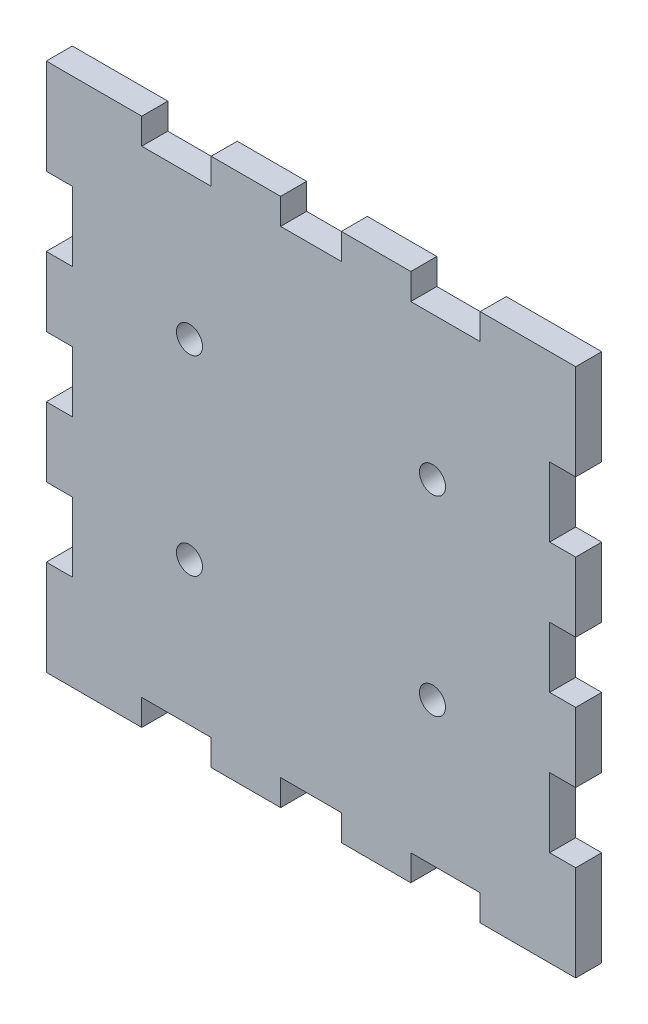
SolidWorks part; units mm, degrees
material "Beech"
ref_plane "Front Plane" through (0, 0, 0) normal (0, 0, 1) x (1, 0, 0)
ref_plane "Top Plane" through (0, 0, 0) normal (0, 1, 0) x (1, 0, 0)
ref_plane "Right Plane" through (0, 0, 0) normal (1, 0, 0) x (0, 0, -1)
sketch "Sketch1" plane through (0, 0, 0) normal (0, 0, 1) x (1, 0, 0)
  line L1 (-30.5, -30.5) -> (30.5, -30.5)
  line L2 (-30.5, -30.5) -> (-30.5, 30.5)
  line L3 (-30.5, 30.5) -> (30.5, 30.5)
  line L4 (30.5, -30.5) -> (30.5, 30.5)
  line L5 (-30.5, -30.5) -> (30.5, 30.5) construction
  line L6 (-30.5, 30.5) -> (30.5, -30.5) construction
  point P0 (0, 0)
  dimension "D1" = 61
  dimension "D2" = 61
extrude "Boss-Extrude1" add sketch "Sketch1" along normal blind 3
sketch "Sketch2" plane through (0, 0, 3) normal (0, 0, 1) x (1, 0, 0)
  line L64 (-27.5, 3.5) -> (-27.5, 11.5)
  line L65 (-27.5, 11.5) -> (-30.5, 11.5)
  line L66 (-30.5, 11.5) -> (-30.5, 3.5)
  line L67 (-30.5, 3.5) -> (-27.5, 3.5)
  line L68 (-27.5, -11.5) -> (-27.5, -3.5)
  line L69 (-27.5, -3.5) -> (-30.5, -3.5)
  line L70 (-30.5, -3.5) -> (-30.5, -11.5)
  line L71 (-30.5, -11.5) -> (-27.5, -11.5)
  line L72 (-27.5, -30.5) -> (-27.5, -19.5)
  line L73 (-27.5, -19.5) -> (-30.5, -19.5)
  line L74 (-30.5, -19.5) -> (-30.5, -30.5)
  line L75 (-30.5, -30.5) -> (-27.5, -30.5)
  line L76 (-19.5, -27.5) -> (-27.5, -27.5)
  line L77 (-27.5, -27.5) -> (-27.5, -30.5)
  line L78 (-27.5, -30.5) -> (-19.5, -30.5)
  line L79 (-19.5, -30.5) -> (-19.5, -27.5)
  line L80 (-3.5, -27.5) -> (-11.5, -27.5)
  line L81 (-11.5, -27.5) -> (-11.5, -30.5)
  line L82 (-11.5, -30.5) -> (-3.5, -30.5)
  line L83 (-3.5, -30.5) -> (-3.5, -27.5)
  line L84 (11.5, -27.5) -> (3.5, -27.5)
  line L85 (3.5, -27.5) -> (3.5, -30.5)
  line L86 (3.5, -30.5) -> (11.5, -30.5)
  line L87 (11.5, -30.5) -> (11.5, -27.5)
  line L88 (27.5, -27.5) -> (19.5, -27.5)
  line L89 (19.5, -27.5) -> (19.5, -30.5)
  line L90 (19.5, -30.5) -> (27.5, -30.5)
  line L91 (27.5, -30.5) -> (27.5, -27.5)
  line L92 (30.5, -30.5) -> (30.5, -19.5)
  line L93 (30.5, -19.5) -> (27.5, -19.5)
  line L94 (27.5, -19.5) -> (27.5, -30.5)
  line L95 (27.5, -30.5) -> (30.5, -30.5)
  line L96 (30.5, -11.5) -> (30.5, -3.5)
  line L97 (30.5, -3.5) -> (27.5, -3.5)
  line L98 (27.5, -3.5) -> (27.5, -11.5)
  line L99 (27.5, -11.5) -> (30.5, -11.5)
  line L100 (30.5, 3.5) -> (30.5, 11.5)
  line L101 (30.5, 11.5) -> (27.5, 11.5)
  line L102 (27.5, 11.5) -> (27.5, 3.5)
  line L103 (27.5, 3.5) -> (30.5, 3.5)
  line L104 (30.5, 19.5) -> (30.5, 30.5)
  line L105 (30.5, 30.5) -> (27.5, 30.5)
  line L106 (27.5, 30.5) -> (27.5, 19.5)
  line L107 (27.5, 19.5) -> (30.5, 19.5)
  line L108 (27.5, 30.5) -> (19.5, 30.5)
  line L109 (19.5, 30.5) -> (19.5, 27.5)
  line L110 (19.5, 27.5) -> (27.5, 27.5)
  line L111 (27.5, 27.5) -> (27.5, 30.5)
  line L112 (11.5, 30.5) -> (3.5, 30.5)
  line L113 (3.5, 30.5) -> (3.5, 27.5)
  line L114 (3.5, 27.5) -> (11.5, 27.5)
  line L115 (11.5, 27.5) -> (11.5, 30.5)
  line L116 (-3.5, 30.5) -> (-11.5, 30.5)
  line L117 (-11.5, 30.5) -> (-11.5, 27.5)
  line L118 (-11.5, 27.5) -> (-3.5, 27.5)
  line L119 (-3.5, 27.5) -> (-3.5, 30.5)
  line L120 (-19.5, 30.5) -> (-27.5, 30.5)
  line L121 (-27.5, 30.5) -> (-27.5, 27.5)
  line L122 (-27.5, 27.5) -> (-19.5, 27.5)
  line L123 (-19.5, 27.5) -> (-19.5, 30.5)
  line L124 (-27.5, 19.5) -> (-27.5, 30.5)
  line L125 (-27.5, 30.5) -> (-30.5, 30.5)
  line L126 (-30.5, 30.5) -> (-30.5, 19.5)
  line L127 (-30.5, 19.5) -> (-27.5, 19.5)
  line L129 (-27.5, -27.5) -> (27.5, -27.5)
  line L130 (-27.5, -27.5) -> (-27.5, 27.5)
  line L131 (-27.5, 27.5) -> (27.5, 27.5)
  line L132 (30.5, -30.5) -> (30.5, 30.5)
  line L133 (30.5, 30.5) -> (-30.5, 30.5)
  line L134 (-30.5, 30.5) -> (-30.5, -30.5)
  line L135 (-30.5, -30.5) -> (30.5, -30.5)
  line L136 (30.5, -30.5) -> (30.5, 30.5)
  line L137 (30.5, 30.5) -> (-30.5, 30.5)
  line L138 (-30.5, 30.5) -> (-30.5, -30.5)
  line L139 (-30.5, -30.5) -> (30.5, -30.5)
  line L140 (27.5, -27.5) -> (27.5, 27.5)
  line L141 (-27.5, -27.5) -> (27.5, 27.5) construction
  line L142 (-27.5, 27.5) -> (27.5, -27.5) construction
  point P6 (0, 0)
  line M9 (30.5, -30.5) -> (30.5, 30.5)
  line M10 (30.5, 30.5) -> (-30.5, 30.5)
  line M11 (-30.5, 30.5) -> (-30.5, -30.5)
  line M12 (-30.5, -30.5) -> (30.5, -30.5)
  dimension "D1" = 0
extrude "Cut-Extrude1" cut sketch "Sketch2" against normal blind 3 contours L65 L130 L127 M11 | L69 L130 L67 M11 | L73 L130 L71 M11 | L129 L79 L81 M12 | L129 L83 L85 M12 | L129 L87 L89 M12 | L140 L93 L99 M9 | L140 L97 L103 M9 | L140 L101 L107 M9 | L115 L131 L109 M10 | L119 L131 L113 M10 | L123 L131 L117 M10
sketch "Sketch3" plane through (0, 0, 3) normal (0, 0, 1) x (1, 0, 0)
  line L1 (-14, -11) -> (14, -11)
  line L2 (-14, -11) -> (-14, 11)
  line L3 (-14, 11) -> (14, 11)
  line L4 (14, -11) -> (14, 11)
  line L5 (-14, -11) -> (14, 11) construction
  line L6 (-14, 11) -> (14, -11) construction
  circle A0 centre (-14, 11) radius 1.5
  circle A1 centre (14, 11) radius 1.5
  circle A2 centre (14, -11) radius 1.5
  circle A3 centre (-14, -11) radius 1.5
  point P0 (0, 0)
  dimension "D3" = 3
  dimension "D1" = 28
  dimension "D2" = 22
extrude "Cut-Extrude2" cut sketch "Sketch3" against normal blind 3 contours L3 A0 L2 | L2 A0 L3 | L4 A1 L3 | L3 A1 L4 | L2 A3 L1 | L1 A3 L2 | L4 A2 L1 | L1 A2 L4
